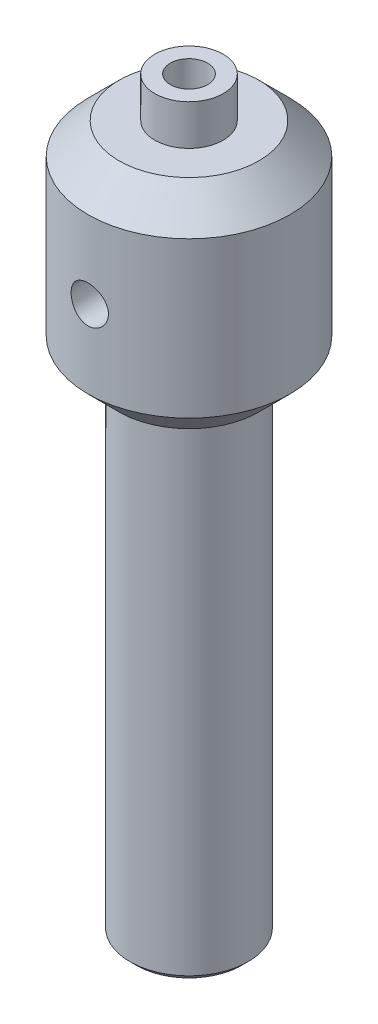
SolidWorks part; units mm, degrees
ref_plane "Front Plane" through (0, 0, 0) normal (0, 0, 1) x (1, 0, 0)
ref_plane "Top Plane" through (0, 0, 0) normal (0, 1, 0) x (1, 0, 0)
ref_plane "Right Plane" through (0, 0, 0) normal (1, 0, 0) x (0, 0, -1)
sketch "Sketch1" plane through (0, 0, 0) normal (0, 0, 1) x (1, 0, 0)
  line L0 (0, 0) -> (19, 0)
  line L1 (19, 0) -> (19, 157)
  line L2 (19, 157) -> (32.5, 157)
  line L3 (32.5, 157) -> (32.5, 227)
  line L4 (32.5, 227) -> (11, 227)
  line L5 (11, 227) -> (11, 240)
  line L6 (11, 240) -> (0, 240)
  line L7 (0, 240) -> (0, 0)
  dimension "D1" = 32.5
  dimension "D2" = 19
  dimension "D3" = 11
  dimension "D4" = 13
  dimension "D5" = 240
  dimension "D6" = 83
revolve "Revolve1" add sketch "Sketch1" angle 360 about L7
chamfer "Chamfer1" distance 10 angle 45 2 edges at (-32.5, 157, 0) (-32.5, 227, 0)
sketch "Sketch2" plane through (0, 0, 0) normal (0, 0, 1) x (1, 0, 0)
  line L0 (11, 240) -> (-11, 240) construction
  circle A0 centre (0, 192) radius 6
  dimension "D1" = 12
  dimension "D2" = 48
extrude "Cut-Extrude1" cut sketch "Sketch2" against normal through all both and the other way through all
hole_wizard "Hole1" positions "Sketch3" profile "Sketch4" legacy
sketch "Sketch3" plane through (0, 240, 0) normal (0, 1, 0) x (1, 0, 0)
  point P0 (0, 0)
sketch "Sketch4" plane through (0, 240, 0) normal (1, 0, 0) x (0, 0, 1)
  line L0 (0, 0) -> (0, 23)
  line L1 (0, 23) -> (6, 23)
  line L2 (6, 23) -> (6, 0)
  line L3 (6, 0) -> (0, 0)
  line L4 (0, 110) -> (0, -10) construction
  dimension "Diameter" = 12
  dimension "Depth" = 23
chamfer "Chamfer2" distance 2 angle 45 1 edges at (-19, 0, 0)
